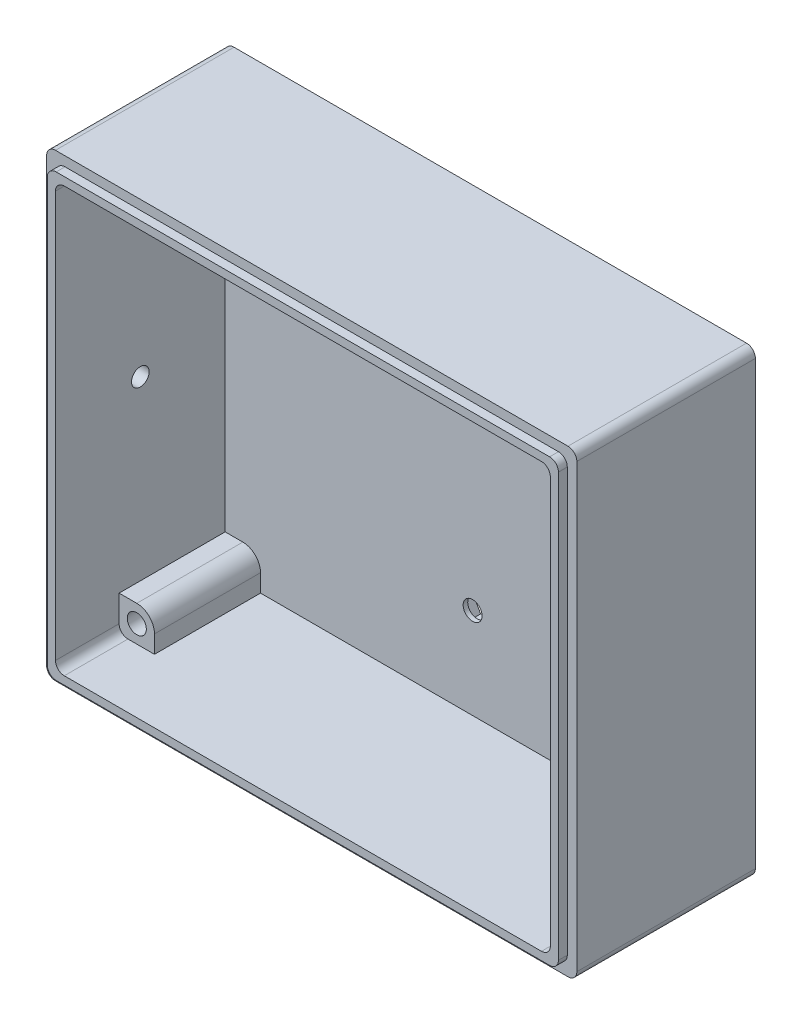
SolidWorks part; units mm, degrees
ref_plane "Front Plane" through (0, 0, 0) normal (0, 0, 1) x (1, 0, 0)
ref_plane "Top Plane" through (0, 0, 0) normal (0, 1, 0) x (1, 0, 0)
ref_plane "Right Plane" through (0, 0, 0) normal (1, 0, 0) x (0, 0, -1)
sketch "Sketch1" plane through (0, 0, 0) normal (0, 0, 1) x (1, 0, 0)
  line L1 (-47.625, -41.275) -> (47.625, -41.275)
  line L2 (-47.625, -41.275) -> (-47.625, 41.275)
  line L3 (-47.625, 41.275) -> (47.625, 41.275)
  line L4 (47.625, -41.275) -> (47.625, 41.275)
  line L5 (-47.625, -41.275) -> (47.625, 41.275) construction
  line L6 (-47.625, 41.275) -> (47.625, -41.275) construction
  point P0 (0, 0)
  dimension "D1" = 82.55
  dimension "3.75" = 95.25
extrude "Boss-Extrude1" add sketch "Sketch1" along normal blind 3.175
sketch "Sketch2" plane through (0, 0, 3.175) normal (0, 0, 1) x (1, 0, 0)
  line L1 (-47.625, -41.275) -> (47.625, -41.275)
  line L2 (-47.625, -41.275) -> (-47.625, 41.275)
  line L3 (-47.625, 41.275) -> (47.625, 41.275)
  line L4 (47.625, -41.275) -> (47.625, 41.275)
  line L5 (-47.625, -41.275) -> (47.625, 41.275) construction
  line L6 (-47.625, 41.275) -> (47.625, -41.275) construction
  line L7 (-44.45, -38.1) -> (44.45, -38.1)
  line L8 (-44.45, -38.1) -> (-44.45, 38.1)
  line L9 (-44.45, 38.1) -> (44.45, 38.1)
  line L10 (44.45, -38.1) -> (44.45, 38.1)
  line L11 (-44.45, -38.1) -> (44.45, 38.1) construction
  line L12 (-44.45, 38.1) -> (44.45, -38.1) construction
  point P0 (0, 0)
  point P7 (0, 0)
  dimension "D1" = 3.175
  dimension "D2" = 3.175
extrude "Boss-Extrude2" add sketch "Sketch2" along normal blind 28.9
sketch "Sketch3" plane through (0, 0, 32.075) normal (0, 0, 1) x (1, 0, 0)
  line L1 (-44.45, -38.1) -> (44.45, -38.1)
  line L2 (-44.45, -38.1) -> (-44.45, 38.1)
  line L3 (-44.45, 38.1) -> (44.45, 38.1)
  line L4 (44.45, -38.1) -> (44.45, 38.1)
  line L5 (-44.45, -38.1) -> (44.45, 38.1) construction
  line L6 (-44.45, 38.1) -> (44.45, -38.1) construction
  line L7 (-45.9105, -39.5605) -> (45.9105, -39.5605)
  line L8 (-45.9105, -39.5605) -> (-45.9105, 39.5605)
  line L9 (-45.9105, 39.5605) -> (45.9105, 39.5605)
  line L10 (45.9105, -39.5605) -> (45.9105, 39.5605)
  line L11 (-45.9105, -39.5605) -> (45.9105, 39.5605) construction
  line L12 (-45.9105, 39.5605) -> (45.9105, -39.5605) construction
  point P0 (0, 0)
  point P7 (0, 0)
  dimension "D1" = 1.4605
  dimension "D2" = 1.4605
extrude "Boss-Extrude3" add sketch "Sketch3" along normal blind 1.5875
fillet "Fillet1" radius 1.5875 12 edges at (44.45, 38.1, 18.4187) (-44.45, 38.1, 18.4187) (-44.45, -38.1, 18.4187) (44.45, -38.1, 18.4187) (-45.9105, 39.5605, 32.8688) (-47.625, 41.275, 16.0375) (45.9105, 39.5605, 32.8688) (47.625, 41.275, 16.0375) (45.9105, -39.5605, 32.8688) (47.625, -41.275, 16.0375) (-45.9105, -39.5605, 32.8688) (-47.625, -41.275, 16.0375)
sketch "Sketch4" plane through (0, 0, 0) normal (0, 0, -1) x (-1, 0, 0)
  line L0 (0, 0) -> (0, 41.275) construction
  line L1 (-46.0375, 41.275) -> (46.0375, 41.275) construction
  line L2 (0, 0) -> (-47.625, 0) construction
  line L3 (-47.625, -39.6875) -> (-47.625, 39.6875) construction
  circle A0 centre (0, 21.75) radius 1.7018
  circle A1 centre (0, -21.75) radius 1.7018
  dimension "D1" = 3.4036
  dimension "D2" = 21.75
extrude "Cut-Extrude1" cut sketch "Sketch4" against normal through all
sketch "Sketch5" plane through (0, 0, 0) normal (0, 0, -1) x (-1, 0, 0)
  line L0 (0, 0) -> (47.625, 0) construction
  line L1 (3.4462, 21.75) -> (1.7231, 24.7345)
  line L2 (1.7231, 24.7345) -> (-1.7231, 24.7345)
  line L3 (-1.7231, 24.7345) -> (-3.4462, 21.75)
  line L4 (-3.4462, 21.75) -> (-1.7231, 18.7655)
  line L5 (-1.7231, 18.7655) -> (1.7231, 18.7655)
  line L6 (1.7231, 18.7655) -> (3.4462, 21.75)
  line L7 (47.625, 39.6875) -> (47.625, -39.6875) construction
  line L8 (1.7231, -18.7655) -> (3.4462, -21.75)
  line L9 (-1.7231, -18.7655) -> (1.7231, -18.7655)
  line L10 (-3.4462, -21.75) -> (-1.7231, -18.7655)
  line L11 (-1.7231, -24.7345) -> (-3.4462, -21.75)
  line L12 (1.7231, -24.7345) -> (-1.7231, -24.7345)
  line L13 (3.4462, -21.75) -> (1.7231, -24.7345)
  circle A0 centre (0, 21.75) radius 2.9845 construction
  dimension "D1" = 5.969
extrude "Cut-Extrude2" cut sketch "Sketch5" against normal blind 2.35
sketch "Sketch7" plane through (0, 0, 3.175) normal (0, 0, 1) x (1, 0, 0)
  line L0 (42.8625, 38.1) -> (-42.8625, 38.1) construction
  line L1 (-44.45, 36.5125) -> (-44.45, -36.5125) construction
  line L2 (44.45, -36.5125) -> (44.45, 36.5125) construction
  line L3 (-42.8625, -38.1) -> (42.8625, -38.1) construction
  line L4 (44.45, -36.5125) -> (44.45, 36.5125)
  line L5 (-42.8625, -38.1) -> (42.8625, -38.1)
  line L6 (42.8625, 38.1) -> (-42.8625, 38.1)
  line L7 (-44.45, 36.5125) -> (-44.45, -36.5125)
  line L8 (-41.275, 31.75) -> (-44.45, 31.75)
  line L9 (-38.1, 34.925) -> (-38.1, 38.1)
  circle A0 centre (-41.275, 34.925) radius 3.175
  arc A1 (44.45, 36.5125) -> (42.8625, 38.1) centre (42.8625, 36.5125) ccw construction
  arc A2 (42.8625, -38.1) -> (44.45, -36.5125) centre (42.8625, -36.5125) ccw construction
  arc A3 (-44.45, -36.5125) -> (-42.8625, -38.1) centre (-42.8625, -36.5125) ccw construction
  arc A4 (-42.8625, 38.1) -> (-44.45, 36.5125) centre (-42.8625, 36.5125) ccw construction
  arc A5 (44.45, 36.5125) -> (42.8625, 38.1) centre (42.8625, 36.5125) ccw
  arc A6 (42.8625, -38.1) -> (44.45, -36.5125) centre (42.8625, -36.5125) ccw
  arc A7 (-44.45, -36.5125) -> (-42.8625, -38.1) centre (-42.8625, -36.5125) ccw
  arc A8 (-42.8625, 38.1) -> (-44.45, 36.5125) centre (-42.8625, 36.5125) ccw
  circle A9 centre (-41.275, 34.925) radius 1.7145
  line M14 (42.8625, 38.1) -> (-42.8625, 38.1)
  arc M15 (-42.8625, 38.1) -> (-44.45, 36.5125) centre (-42.8625, 36.5125) ccw
  line M16 (-44.45, 36.5125) -> (-44.45, -36.5125)
  dimension "D1" = 6.35
  dimension "D2" = 3.429
extrude "Boss-Extrude4" add sketch "Sketch7" along normal blind 19.05 contours A0 M14 M15 M16 | A0 L7 L8 | A0 L9 L6 | A0 A9
sketch "Sketch8" plane through (0, 0, 22.225) normal (0, 0, 1) x (1, 0, 0)
  circle A0 centre (-41.275, 34.925) radius 1.7145 construction
  circle A1 centre (-41.275, 34.925) radius 1.7145
extrude "Cut-Extrude3" cut sketch "Sketch8" against normal through all
mirror "Mirror1" about plane through (0, 0, 0) normal (1, 0, 0) of "Cut-Extrude3", "Boss-Extrude4" second plane through (0, 0, 0) second plane normal (0, 1, 0)
sketch "Sketch9" plane through (0, 0, 0) normal (0, 0, -1) x (-1, 0, 0)
  line L1 (-37.8282, 34.925) -> (-39.5516, 37.91)
  line L2 (-39.5516, 37.91) -> (-42.9984, 37.91)
  line L3 (-42.9984, 37.91) -> (-44.7218, 34.925)
  line L4 (-44.7218, 34.925) -> (-42.9984, 31.94)
  line L5 (-42.9984, 31.94) -> (-39.5516, 31.94)
  line L6 (-39.5516, 31.94) -> (-37.8282, 34.925)
  circle A0 centre (-41.275, 34.925) radius 2.985 construction
  dimension "D1" = 5.97
extrude "Cut-Extrude4" cut sketch "Sketch9" against normal blind 2.4
mirror "Mirror2" about plane through (0, 0, 0) normal (1, 0, 0) of "Cut-Extrude4" second plane through (0, 0, 0) second plane normal (0, 1, 0)
sketch "Sketch10" plane through (-44.45, 0, 0) normal (1, 0, 0) x (0, 0, -1)
  line L0 (-3.175, 0) -> (-33.6625, 0)
  line L1 (-3.175, 31.75) -> (-3.175, -31.75) construction
  line L2 (-33.6625, 36.5125) -> (-33.6625, -36.5125) construction
  circle A0 centre (-18.4188, 0) radius 1.5875
  dimension "D1" = 3.175
extrude "Cut-Extrude5" cut sketch "Sketch10" against normal through all contours L0 A0 | L0 A0
